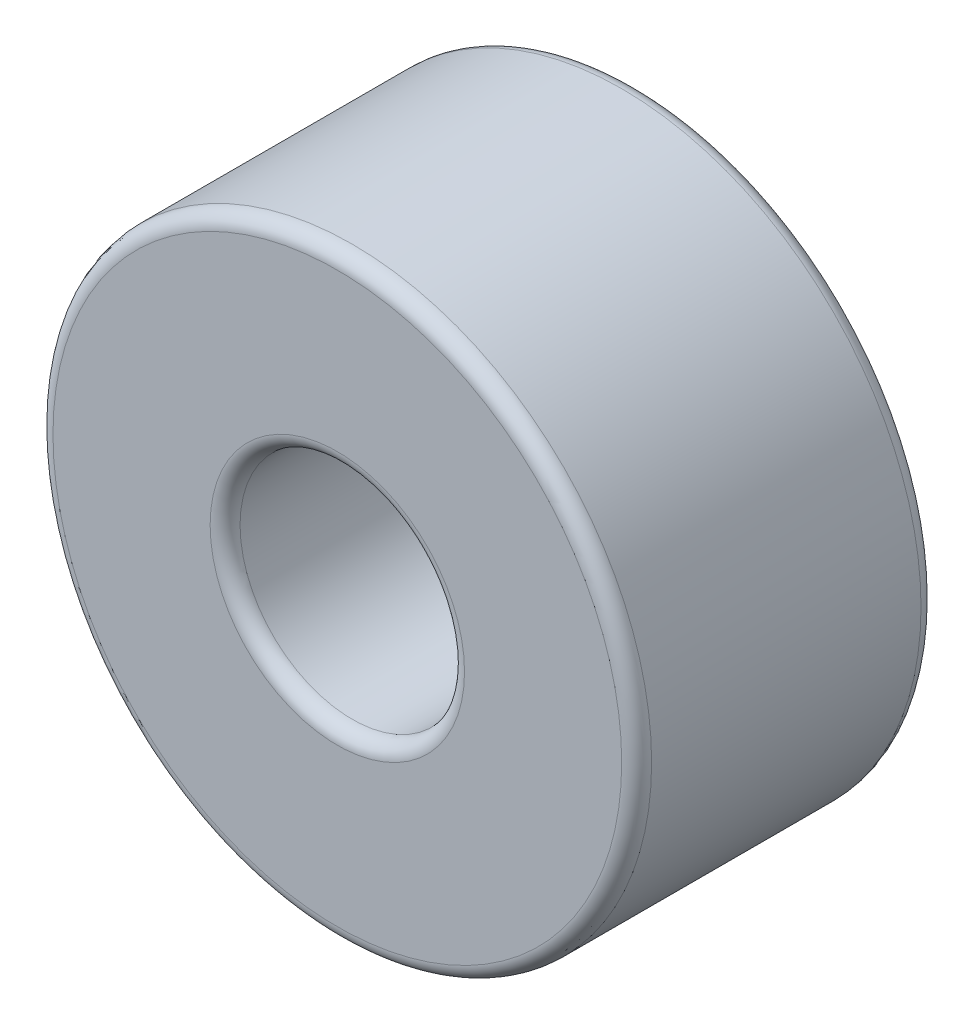
SolidWorks part; units mm, degrees
material "Хромистая нержавеющая сталь"
ref_plane "Спереди" through (0, 0, 0) normal (0, 0, 1) x (1, 0, 0)
ref_plane "Сверху" through (0, 0, 0) normal (0, 1, 0) x (1, 0, 0)
ref_plane "Справа" through (0, 0, 0) normal (1, 0, 0) x (0, 0, -1)
sketch "Эскиз1" plane through (0, 0, 0) normal (0, 0, 1) x (1, 0, 0)
  circle A0 centre (0, 0) radius 1.5
  circle A1 centre (0, 0) radius 4
  dimension "D1" = 3
  dimension "D2" = 8
extrude "Бобышка-Вытянуть1" add sketch "Эскиз1" along normal blind 4 contours A1 | A0
fillet "Скругление1" radius 0.2 4 edges at (1.5, 0, 0) (1.5, 0, 4) (4, 0, 0) (4, 0, 4)
